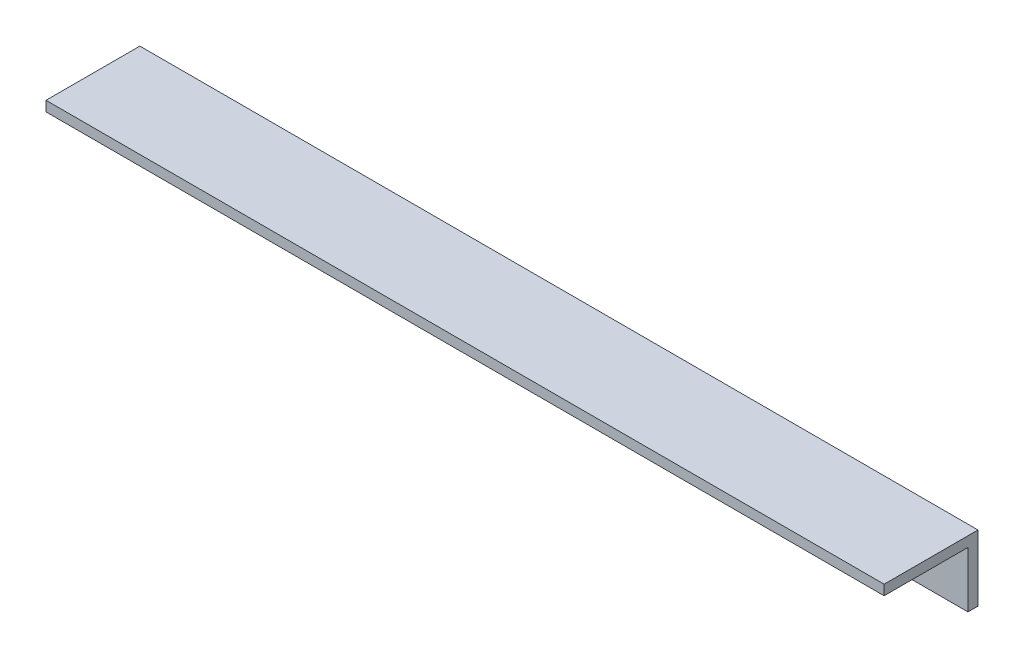
SolidWorks part; units mm, degrees
ref_plane "Ebene vorne" through (0, 0, 0) normal (0, 0, 1) x (1, 0, 0)
ref_plane "Ebene oben" through (0, 0, 0) normal (0, 1, 0) x (1, 0, 0)
ref_plane "Ebene rechts" through (0, 0, 0) normal (1, 0, 0) x (0, 0, -1)
sketch "Skizze1" plane through (0, 0, 0) normal (1, 0, 0) x (0, 0, -1)
  line L0 (0, 0) -> (0, 100)
  line L1 (0, 100) -> (-150, 100)
  line L2 (18, 0) -> (18, 118)
  line L3 (18, 118) -> (-150, 118)
  line L4 (0, 0) -> (18, 0)
  line L5 (-150, 100) -> (-150, 118)
  dimension "D1" = 100
  dimension "D2" = 150
  dimension "D3" = 18
extrude "Aufsatz-Linear austragen1" add sketch "Skizze1" along normal blind 1500
